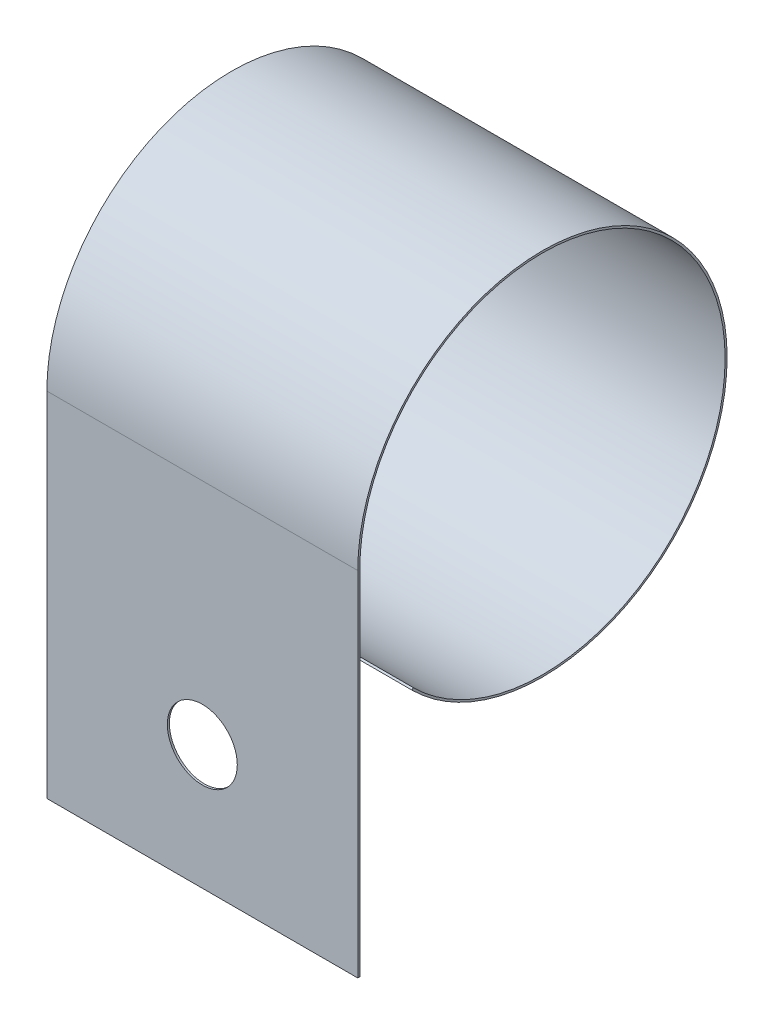
SolidWorks part; units mm, degrees
material "SUS304"
ref_plane "Front Plane" through (0, 0, 0) normal (0, 0, 1) x (1, 0, 0)
ref_plane "Top Plane" through (0, 0, 0) normal (0, 1, 0) x (1, 0, 0)
ref_plane "Right Plane" through (0, 0, 0) normal (1, 0, 0) x (0, 0, -1)
sketch "Sketch1" plane through (0, 0, 0) normal (1, 0, 0) x (0, -1, 0)
  line L7 (0, 0) -> (0, -11.75) construction
  line L8 (8.4004, -8.4004) -> (0, 0) construction
  line L9 (8.4004, -8.4004) -> (8.3085, -8.3085)
  line L10 (22.7, -11.88) -> (0, -11.88)
  line L11 (22.7, -11.75) -> (22.7, -11.88)
  line L12 (22.7, -11.75) -> (0, -11.75)
  circle A3 centre (0, 0) radius 11.75 construction
  arc A4 (0, -11.88) -> (8.4004, -8.4004) centre (0, 0) cw
  arc A5 (0, -11.75) -> (8.3085, -8.3085) centre (0, 0) cw
  dimension "MSM_1" = 23.5
  dimension "MSM_5" = 22.7
  dimension "FIX_1" = 45
  dimension "Accessories Plate Thickness" = 0.13
extrude "Boss-Extrude1" add sketch "Sketch1" along normal mid plane 20
sketch "Sketch2" plane through (0, 0, 11.88) normal (0, 0, -1) x (-1, 0, 0)
  circle A0 centre (0, -14.7) radius 2.25
  dimension "D_s" = 4.5
  dimension "Y" = 8
extrude "Cut-Extrude1" cut sketch "Sketch2" along normal up to next
